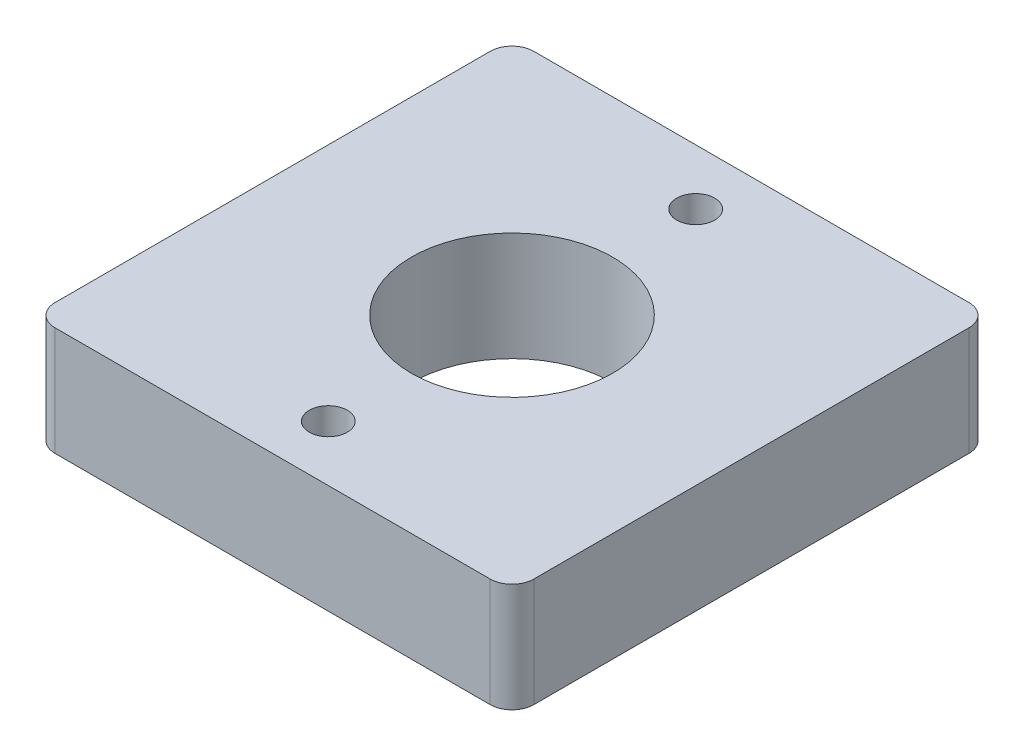
SolidWorks part; units mm, degrees
ref_plane "Alzado" through (0, 0, 0) normal (0, 0, 1) x (1, 0, 0)
ref_plane "Planta" through (0, 0, 0) normal (0, 1, 0) x (1, 0, 0)
ref_plane "Vista lateral" through (0, 0, 0) normal (1, 0, 0) x (0, 0, -1)
sketch "Croquis1" plane through (0, 0, 0) normal (0, 1, 0) x (1, 0, 0)
  line L1 (-22, -22) -> (22, -22)
  line L2 (-22, -22) -> (-22, 22)
  line L3 (-22, 22) -> (22, 22)
  line L4 (22, -22) -> (22, 22)
  line L5 (-22, -22) -> (22, 22) construction
  line L6 (-22, 22) -> (22, -22) construction
  circle A0 centre (0, 0) radius 9.25
  point P0 (0, 0)
  dimension "D3" = 18.5
  dimension "D1" = 44
  dimension "D2" = 44
extrude "Saliente-Extruir1" add sketch "Croquis1" along normal blind 10
sketch "Croquis2" plane through (0, 10, 0) normal (0, 1, 0) x (1, 0, 0)
  line L0 (-22, 22) -> (-22, -22) construction
  line L1 (22, -11.75) -> (-22, -11.75) construction
  line L2 (22, -11.75) -> (22, 11.75) construction
  line L3 (22, 11.75) -> (-22, 11.75) construction
  line L4 (-22, -11.75) -> (-22, 11.75) construction
  line L5 (22, -11.75) -> (-22, 11.75) construction
  line L6 (22, 11.75) -> (-22, -11.75) construction
  line L7 (-22, 16.88) -> (22, 16.88) construction
  line L8 (22, -22) -> (22, 22) construction
  line L9 (0, 22) -> (0, -22) construction
  line L10 (22, 22) -> (-22, 22) construction
  line L11 (-22, -22) -> (22, -22) construction
  line L12 (-22, -16.88) -> (22, -16.88) construction
  circle A0 centre (0, 16.88) radius 1.75
  circle A1 centre (0, -16.88) radius 1.75
  point P0 (0, 0)
  point P18 (0, 16.88)
  point P19 (0, -16.88)
  dimension "D4" = 3.5
  dimension "D5" = 3.5
  dimension "D1" = 23.5
  dimension "D2" = 5.13
  dimension "D3" = 5.13
extrude "Cortar-Extruir1" cut sketch "Croquis2" against normal through all
fillet "Redondeo1" radius 2 4 edges at (22, 5, -22) (22, 5, 22) (-22, 5, 22) (-22, 5, -22)
